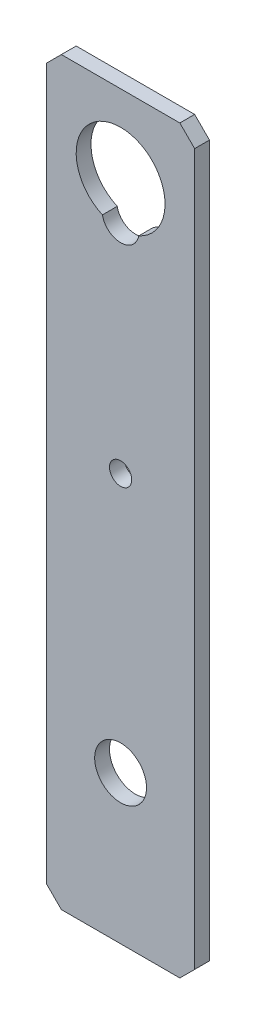
SolidWorks part; units mm, degrees
ref_plane "Front Plane" through (0, 0, 0) normal (0, 0, 1) x (1, 0, 0)
ref_plane "Top Plane" through (0, 0, 0) normal (0, 1, 0) x (1, 0, 0)
ref_plane "Right Plane" through (0, 0, 0) normal (1, 0, 0) x (0, 0, -1)
sketch "Sketch1" plane through (0, 0, 0) normal (0, 0, 1) x (1, 0, 0)
  line L1 (-10, 50) -> (10, 50)
  line L2 (-10, 50) -> (-10, -50)
  line L3 (-10, -50) -> (10, -50)
  line L4 (10, 50) -> (10, -50)
  line L5 (-10, 50) -> (10, -50) construction
  line L6 (-10, -50) -> (10, 50) construction
  point P0 (0, 0)
  dimension "D1" = 100
  dimension "D2" = 20
extrude "Boss-Extrude1" add sketch "Sketch1" along normal blind 2
sketch "Sketch2" plane through (0, 0, 2) normal (0, 0, 1) x (1, 0, 0)
  line L0 (0, 50) -> (0, -50) construction
  line L1 (10, 50) -> (-10, 50) construction
  line L2 (-10, -50) -> (10, -50) construction
  arc A0 (2.4545, 34.025) -> (-2.4545, 34.025) centre (0, 39.5) ccw
  circle A1 centre (0, 5) radius 1.5
  circle A2 centre (0, -30) radius 3.5
  arc A3 (-2.4545, 34.025) -> (2.4545, 34.025) centre (0, 34.5) ccw
  dimension "D1" = 7
  dimension "D2" = 12
  dimension "D3" = 3
  dimension "D4" = 20
  dimension "D7" = 5
  dimension "D5" = 55
  dimension "D6" = 10.5
  dimension "D8" = 5
extrude "Cut-Extrude1" cut sketch "Sketch2" against normal up to next
chamfer "Chamfer1" distance 2 angle 45 4 edges at (10, 50, 1) (10, -50, 1) (-10, -50, 1) (-10, 50, 1)
